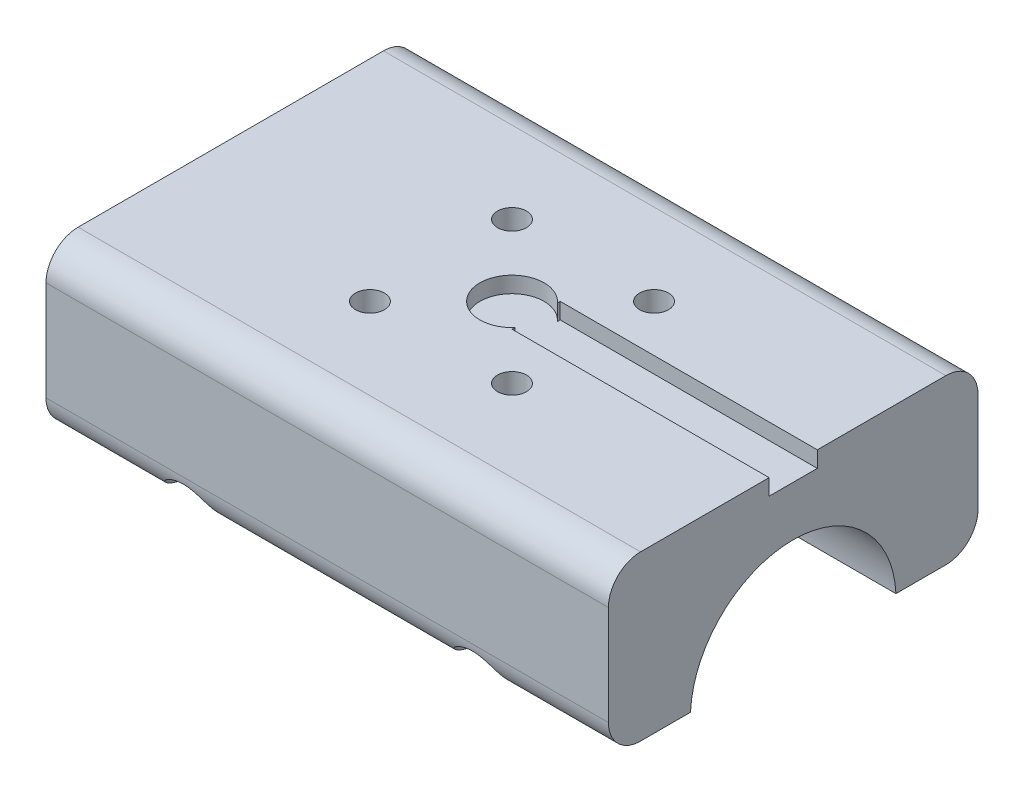
SolidWorks part; units mm, degrees
ref_plane "Front Plane" through (0, 0, 0) normal (0, 0, 1) x (1, 0, 0)
ref_plane "Top Plane" through (0, 0, 0) normal (0, 1, 0) x (1, 0, 0)
ref_plane "Right Plane" through (0, 0, 0) normal (1, 0, 0) x (0, 0, -1)
sketch "Sketch1" plane through (0, 0, 0) normal (1, 0, 0) x (0, 0, -1)
  line L0 (-19, 0.6) -> (19, 0.6)
  line L1 (23, 4.6) -> (23, 17)
  line L2 (19, 21) -> (-19, 21)
  line L3 (-23, 17) -> (-23, 4.6)
  arc A0 (19, 0.6) -> (23, 4.6) centre (19, 4.6) ccw
  arc A1 (23, 17) -> (19, 21) centre (19, 17) ccw
  arc A2 (-19, 21) -> (-23, 17) centre (-19, 17) ccw
  arc A3 (-23, 4.6) -> (-19, 0.6) centre (-19, 4.6) ccw
extrude "Boss-Extrude1" add sketch "Sketch1" along normal mid plane 70
sketch "Sketch2" plane through (0, 0, 0) normal (1, 0, 0) x (0, 0, -1)
  circle A0 centre (0, 0) radius 12.8
extrude "Cut-Extrude1" cut sketch "Sketch2" against normal through all and the other way through all
ref_plane "Plane1" through (0, 0.6, 0) normal (0, 1, 0) x (1, 0, 0)
sketch "Sketch3" plane through (0, 0.6, 0) normal (0, 1, 0) x (1, 0, 0)
  circle A0 centre (28, -17.5) radius 2
  circle A1 centre (28, 17.5) radius 2
  circle A2 centre (-28, -17.5) radius 2
  circle A3 centre (-28, 17.5) radius 2
extrude "Cut-Extrude2" cut sketch "Sketch3" along normal blind 7.5
sketch "Sketch4" plane through (0, 0, 0) normal (0, 1, 0) x (1, 0, 0)
  circle A0 centre (8.84, -8.84) radius 3.75
  circle A1 centre (8.84, 8.84) radius 3.75
  circle A2 centre (-8.84, -8.84) radius 3.75
  circle A3 centre (-8.84, 8.84) radius 3.75
extrude "Cut-Extrude3" cut sketch "Sketch4" along normal blind 16.5
sketch "Sketch5" plane through (0, 0, 0) normal (0, 1, 0) x (1, 0, 0)
  circle A0 centre (8.84, -8.84) radius 1.8
  circle A1 centre (8.84, 8.84) radius 1.8
  circle A2 centre (-8.84, -8.84) radius 1.8
  circle A3 centre (-8.84, 8.84) radius 1.8
extrude "Cut-Extrude4" cut sketch "Sketch5" along normal blind 22
ref_plane "Plane2" through (0, 21, 0) normal (0, 1, 0) x (1, 0, 0)
sketch "Sketch6" plane through (0, 21, 0) normal (0, 1, 0) x (1, 0, 0)
  circle A0 centre (0, 0) radius 4
extrude "Cut-Extrude5" cut sketch "Sketch6" against normal blind 2
ref_plane "Plane3" through (0, 21, 0) normal (0, 1, 0) x (1, 0, 0)
sketch "Sketch7" plane through (0, 21, 0) normal (0, 1, 0) x (1, 0, 0)
  line L0 (3, 3) -> (35, 3)
  line L1 (35, 3) -> (35, -3)
  line L2 (35, -3) -> (3, -3)
  line L3 (3, -3) -> (3, 3)
extrude "Cut-Extrude6" cut sketch "Sketch7" against normal blind 2
sketch "Sketch8" plane through (0, 0, 0) normal (0, 0, 1) x (1, 0, 0)
  circle A0 centre (18, 0) radius 1.8
  circle A1 centre (-18, 0) radius 1.8
extrude "Cut-Extrude7" cut sketch "Sketch8" against normal through all and the other way through all
ref_plane "Plane4" through (0, 0, 23) normal (0, 0, 1) x (1, 0, 0)
sketch "Sketch9" plane through (0, 0, 23) normal (0, 0, 1) x (1, 0, 0)
  circle A0 centre (18, 0) radius 3.75
  circle A1 centre (-18, 0) radius 3.75
extrude "Cut-Extrude8" cut sketch "Sketch9" against normal blind 5
ref_plane "Plane5" through (0, 0, -23) normal (0, 0, 1) x (1, 0, 0)
sketch "Sketch10" plane through (0, 0, -23) normal (0, 0, 1) x (1, 0, 0)
  line L0 (20.85, 1.6454) -> (18, 3.2909)
  line L1 (18, 3.2909) -> (15.15, 1.6454)
  line L2 (15.15, 1.6454) -> (15.15, -1.6454)
  line L3 (15.15, -1.6454) -> (18, -3.2909)
  line L4 (18, -3.2909) -> (20.85, -1.6454)
  line L5 (20.85, -1.6454) -> (20.85, 1.6454)
  line L6 (-15.15, 1.6454) -> (-18, 3.2909)
  line L7 (-18, 3.2909) -> (-20.85, 1.6454)
  line L8 (-20.85, 1.6454) -> (-20.85, -1.6454)
  line L9 (-20.85, -1.6454) -> (-18, -3.2909)
  line L10 (-18, -3.2909) -> (-15.15, -1.6454)
  line L11 (-15.15, -1.6454) -> (-15.15, 1.6454)
extrude "Cut-Extrude9" cut sketch "Sketch10" along normal blind 8
